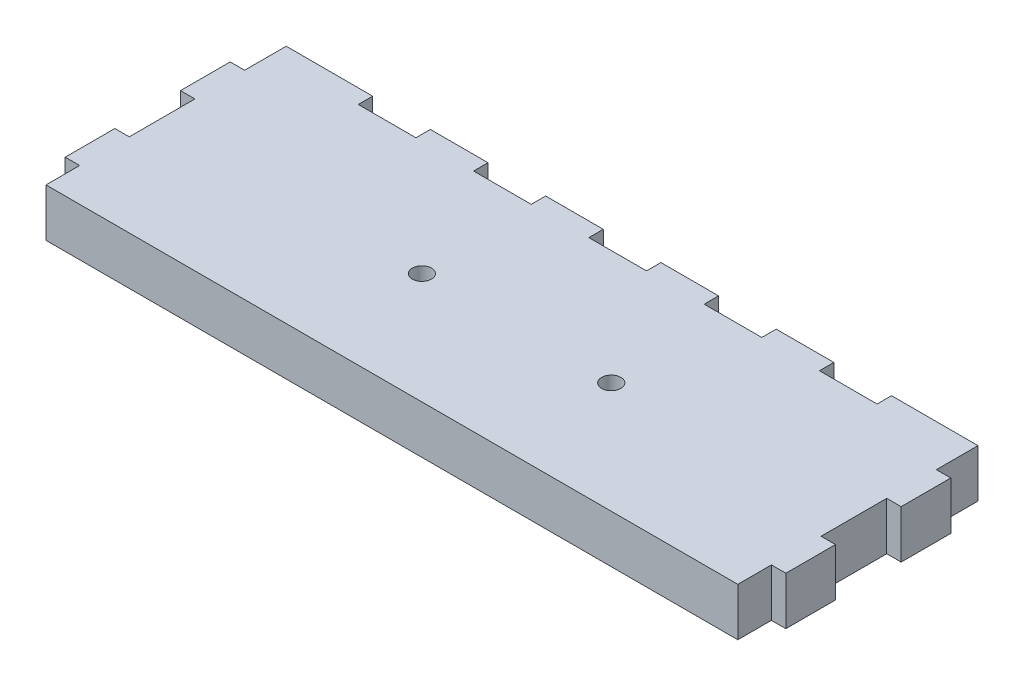
SolidWorks part; units mm, degrees
ref_plane "Front Plane" through (0, 0, 0) normal (0, 0, 1) x (1, 0, 0)
ref_plane "Top Plane" through (0, 0, 0) normal (0, 1, 0) x (1, 0, 0)
ref_plane "Right Plane" through (0, 0, 0) normal (1, 0, 0) x (0, 0, -1)
sketch "Sketch1" plane through (0, 0, 0) normal (0, 1, 0) x (1, 0, 0)
  line L149 (-32.8129, 69.7037) -> (-20.8129, 69.7037)
  line L150 (69.1871, 64.0367) -> (72.1871, 64.0367)
  line L151 (-74.8129, 72.7037) -> (-56.8129, 72.7037)
  line L152 (-74.8129, 72.7037) -> (-74.8129, 69.7037)
  line L153 (-56.8129, 72.7037) -> (-56.8129, 69.7037)
  line L154 (-56.8129, 69.7037) -> (-44.8129, 69.7037)
  line L155 (-74.8129, 69.7037) -> (-74.8129, 64.0367)
  line L156 (69.1871, 69.7037) -> (69.1871, 64.0367)
  line L157 (-77.8129, 64.0367) -> (-74.8129, 64.0367)
  line L158 (-77.8129, 64.0367) -> (-77.8129, 53.7037)
  line L159 (-77.8129, 53.7037) -> (-74.8129, 53.7037)
  line L160 (72.1871, 64.0367) -> (72.1871, 53.7037)
  line L161 (-74.8129, 53.7037) -> (-74.8129, 40.0367)
  line L162 (69.1871, 53.7037) -> (69.1871, 40.0367)
  line L163 (-77.8129, 40.0367) -> (-74.8129, 40.0367)
  line L164 (-77.8129, 40.0367) -> (-77.8129, 29.7037)
  line L165 (-77.8129, 29.7037) -> (-74.8129, 29.7037)
  line L166 (72.1871, 40.0367) -> (72.1871, 29.7037)
  line L167 (-74.8129, 29.7037) -> (-74.8129, 22.7037)
  line L168 (-74.8129, 22.7037) -> (69.1871, 22.7037)
  line L169 (69.1871, 29.7037) -> (69.1871, 22.7037)
  line L170 (-44.8129, 72.7037) -> (-32.8129, 72.7037)
  line L171 (-44.8129, 72.7037) -> (-44.8129, 69.7037)
  line L172 (-32.8129, 72.7037) -> (-32.8129, 69.7037)
  line L173 (-20.8129, 72.7037) -> (-8.8129, 72.7037)
  line L174 (-20.8129, 72.7037) -> (-20.8129, 69.7037)
  line L175 (-8.8129, 72.7037) -> (-8.8129, 69.7037)
  line L176 (3.1871, 72.7037) -> (15.1871, 72.7037)
  line L177 (3.1871, 72.7037) -> (3.1871, 69.7037)
  line L178 (15.1871, 72.7037) -> (15.1871, 69.7037)
  line L179 (27.1871, 72.7037) -> (39.1871, 72.7037)
  line L180 (27.1871, 72.7037) -> (27.1871, 69.7037)
  line L181 (39.1871, 72.7037) -> (39.1871, 69.7037)
  line L182 (51.1871, 72.7037) -> (69.1871, 72.7037)
  line L183 (51.1871, 72.7037) -> (51.1871, 69.7037)
  line L184 (69.1871, 72.7037) -> (69.1871, 69.7037)
  line L185 (69.1871, 53.7037) -> (72.1871, 53.7037)
  line L186 (69.1871, 40.0367) -> (72.1871, 40.0367)
  line L187 (69.1871, 29.7037) -> (72.1871, 29.7037)
  line L188 (-8.8129, 69.7037) -> (3.1871, 69.7037)
  line L189 (15.1871, 69.7037) -> (27.1871, 69.7037)
  line L190 (39.1871, 69.7037) -> (51.1871, 69.7037)
extrude "Boss-Extrude1" add sketch "Sketch1" along normal blind 10 separate body
sketch "Sketch2" plane through (0, 10, 0) normal (0, 1, 0) x (1, 0, 0)
  circle A0 centre (-19.7044, 45.8373) radius 1.9978
  circle A1 centre (19.7066, 45.8414) radius 2
extrude "Cut-Extrude1" cut sketch "Sketch2" against normal through all
